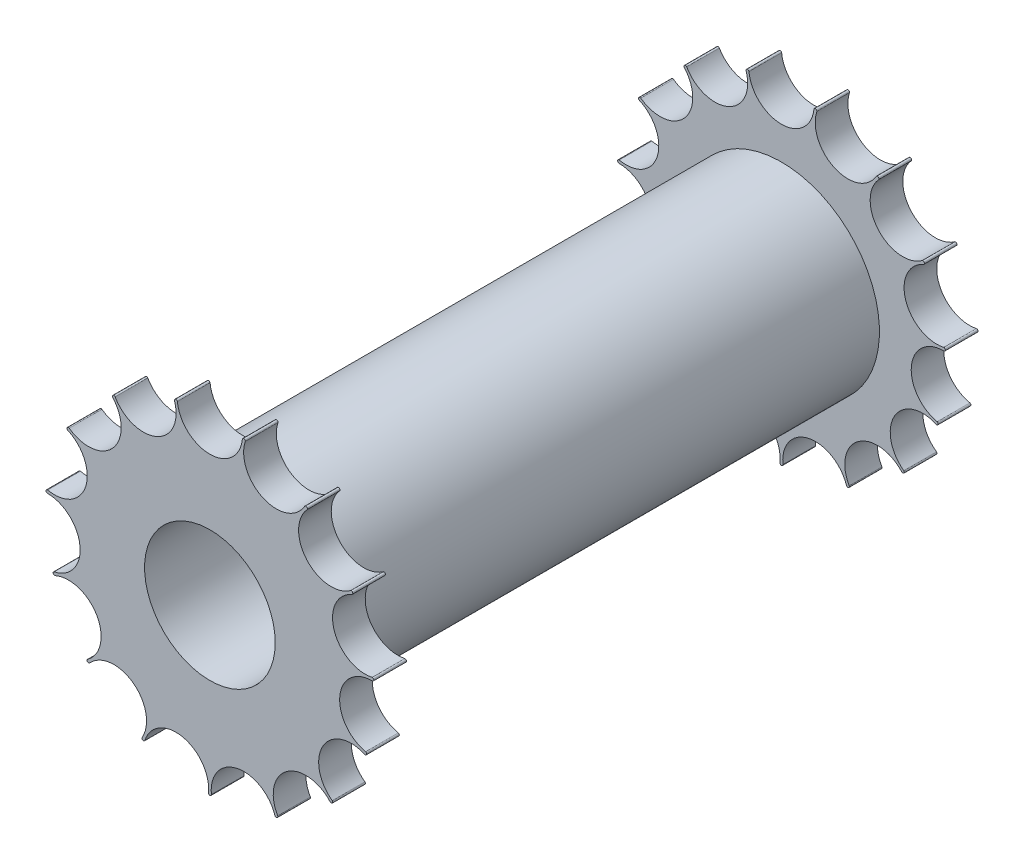
SolidWorks part; units mm, degrees
material "Stainless Steel (ferritic)"
ref_plane "Front" through (0, 0, 0) normal (0, 0, 1) x (1, 0, 0)
ref_plane "Top" through (0, 0, 0) normal (0, 1, 0) x (1, 0, 0)
ref_plane "Right" through (0, 0, 0) normal (1, 0, 0) x (0, 0, -1)
sketch "Sketch1" plane through (0, 0, 0) normal (0, 0, 1) x (1, 0, 0)
  circle A0 centre (0, 0) radius 10
extrude "Boss-Extrude1" add sketch "Sketch1" along normal blind 37
sketch "Sketch2" plane through (0, 0, 37) normal (0, 0, 1) x (1, 0, 0)
  circle A0 centre (0, 0) radius 10
  circle A1 centre (0, 10) radius 2
  circle A2 centre (4.0674, 9.1355) radius 2
  circle A3 centre (7.4314, 6.6913) radius 2
  circle A4 centre (9.5106, 3.0902) radius 2
  circle A5 centre (9.9452, -1.0453) radius 2
  circle A6 centre (8.6603, -5) radius 2
  circle A7 centre (5.8779, -8.0902) radius 2
  circle A8 centre (2.0791, -9.7815) radius 2
  circle A9 centre (-2.0791, -9.7815) radius 2
  circle A10 centre (-5.8779, -8.0902) radius 2
  circle A11 centre (-8.6603, -5) radius 2
  circle A12 centre (-9.9452, -1.0453) radius 2
  circle A13 centre (-9.5106, 3.0902) radius 2
  circle A14 centre (-7.4314, 6.6913) radius 2
  circle A15 centre (-4.0674, 9.1355) radius 2
  point P35 (0, 0)
  circle M1 centre (0, 0) radius 10
extrude "Cut-Extrude1" cut sketch "Sketch2" against normal blind 40 and the other way blind 10 contours A15 M1 | A14 M1 | A13 M1 | A11 M1 | A10 M1 | A9 M1 | A8 M1 | A7 M1 | A6 M1 | A5 M1 | A4 M1 | A3 M1 | A2 M1 | A1 M1 | A12
sketch "Sketch3" plane through (0, 0, 0) normal (0, 0, 1) x (1, 0, 0)
  line L0 (2.1681, 9.7621) -> (1.99, 9.8)
  line L1 (5.9513, 8.0363) -> (5.804, 8.1433)
  line L2 (8.7054, 4.9209) -> (8.6144, 5.0786)
  line L3 (9.9543, 0.9547) -> (9.9353, 1.1358)
  line L4 (9.482, -3.1766) -> (9.5383, -3.0035)
  line L5 (7.3702, -6.7587) -> (7.4921, -6.6234)
  line L6 (3.984, -9.1721) -> (4.1504, -9.098)
  line L7 (-0.091, -9.9996) -> (0.091, -9.9996)
  line L8 (-4.1504, -9.098) -> (-3.984, -9.1721)
  line L9 (-7.4921, -6.6234) -> (-7.3702, -6.7587)
  line L10 (-9.5383, -3.0035) -> (-9.482, -3.1766)
  line L11 (-9.9353, 1.1358) -> (-9.9543, 0.9547)
  line L12 (-8.6144, 5.0786) -> (-8.7054, 4.9209)
  line L13 (-5.804, 8.1433) -> (-5.9513, 8.0363)
  line L14 (-1.99, 9.8) -> (-2.1681, 9.7621)
  arc A0 (1.99, 9.8) -> (2.1681, 9.7621) centre (2.079, 9.7811) cw
  arc A1 (5.804, 8.1433) -> (5.9513, 8.0363) centre (5.8776, 8.0898) cw
  arc A2 (8.6144, 5.0786) -> (8.7054, 4.9209) centre (8.6599, 4.9998) cw
  arc A3 (9.9353, 1.1358) -> (9.9543, 0.9547) centre (9.9448, 1.0452) cw
  arc A4 (9.5383, -3.0035) -> (9.482, -3.1766) centre (9.5102, -3.09) cw
  arc A5 (7.4921, -6.6234) -> (7.3702, -6.7587) centre (7.4311, -6.691) cw
  arc A6 (4.1504, -9.098) -> (3.984, -9.1721) centre (4.0672, -9.1351) cw
  arc A7 (0.091, -9.9996) -> (-0.091, -9.9996) centre (0, -9.9996) cw
  arc A8 (-3.984, -9.1721) -> (-4.1504, -9.098) centre (-4.0672, -9.1351) cw
  arc A9 (-7.3702, -6.7587) -> (-7.4921, -6.6234) centre (-7.4311, -6.691) cw
  arc A10 (-9.482, -3.1766) -> (-9.5383, -3.0035) centre (-9.5102, -3.09) cw
  arc A11 (-9.9543, 0.9547) -> (-9.9353, 1.1358) centre (-9.9448, 1.0452) cw
  arc A12 (-8.7054, 4.9209) -> (-8.6144, 5.0786) centre (-8.6599, 4.9998) cw
  arc A13 (-5.9513, 8.0363) -> (-5.804, 8.1433) centre (-5.8776, 8.0898) cw
  arc A14 (-2.1681, 9.7621) -> (-1.99, 9.8) centre (-2.079, 9.7811) cw
  point P50 (0, 0)
extrude "Boss-Extrude3" add sketch "Sketch3" along normal blind 37
sketch "Sketch4" plane through (0, 0, 37) normal (0, 0, 1) x (1, 0, 0)
  circle A0 centre (0, 0) radius 4
extrude "Cut-Extrude2" cut sketch "Sketch4" against normal blind 40
sketch "Sketch6" plane through (0, 0, 0) normal (1, 0, 0) x (0, 0, -1)
  line L0 (-35, -12.8628) -> (-2, -12.8628)
  line L1 (-10.741, 0) -> (-25.2891, 0) construction
  line L2 (-35, -12.8628) -> (-35, -5.9996)
  line L3 (-35, -5.9996) -> (-2, -5.9996)
  line L4 (-2, -5.9996) -> (-2, -12.8628)
  line L5 (-37, -9.9996) -> (0, -9.9996) construction
  dimension "D1" = 4
revolve "Cut-Revolve7" cut sketch "Sketch6" angle 360 about L1
